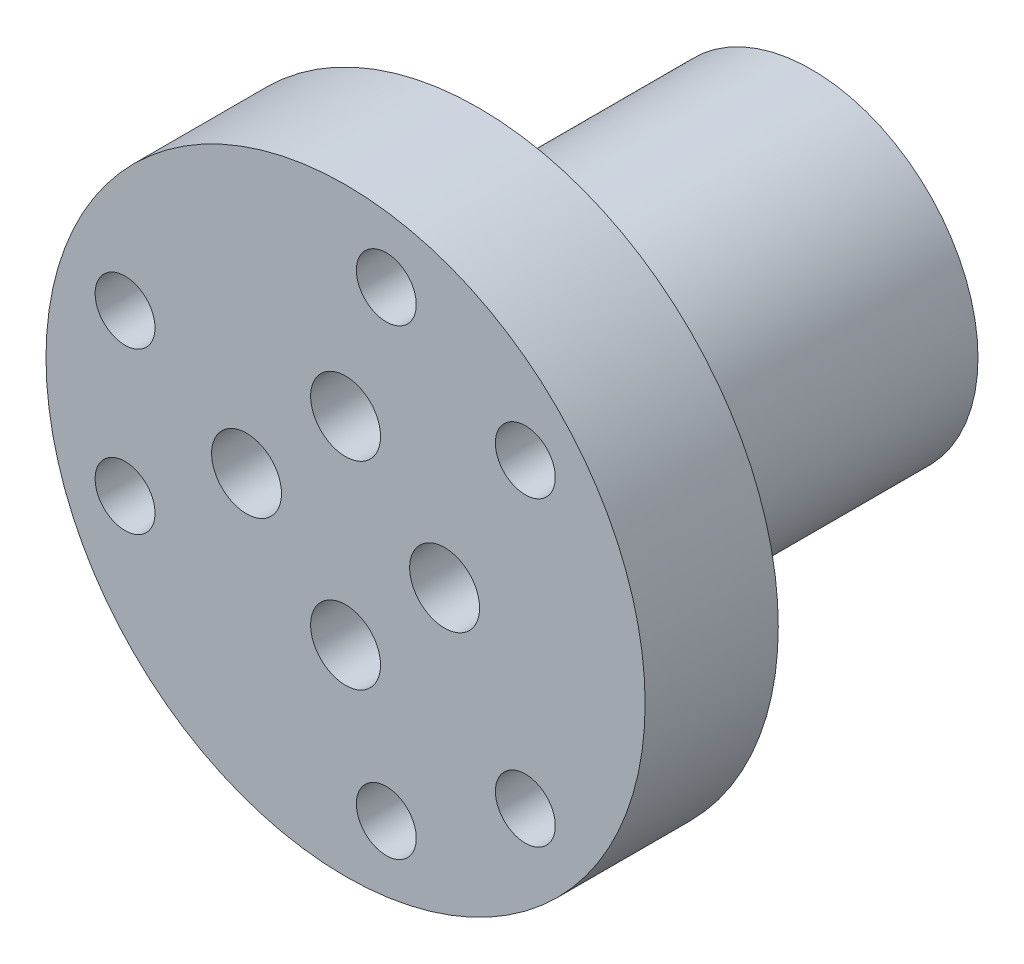
SolidWorks part; units mm, degrees
ref_plane "정면" through (0, 0, 0) normal (0, 0, 1) x (1, 0, 0)
ref_plane "윗면" through (0, 0, 0) normal (0, 1, 0) x (1, 0, 0)
ref_plane "우측면" through (0, 0, 0) normal (1, 0, 0) x (0, 0, -1)
sketch "스케치1" plane through (0, 0, 0) normal (0, 0, 1) x (1, 0, 0)
  line L0 (0, 0) -> (-14.1, 0) construction
  line L1 (0, 0) -> (-13.2497, 4.8225) construction
  circle A0 centre (0, 0) radius 18
  circle A1 centre (0, 5.95) radius 1.3
  circle A2 centre (5.95, 0) radius 1.3
  circle A3 centre (0, -5.95) radius 1.3
  circle A4 centre (-5.95, 0) radius 1.3
  circle A5 centre (0, 0) radius 14.1 construction
  circle A6 centre (-13.2497, 4.8225) radius 1.6
  circle A7 centre (-13.2497, -4.8225) radius 1.6
  circle A8 centre (10.8012, 9.0633) radius 1.6
  circle A9 centre (2.4484, 13.8858) radius 1.6
  circle A10 centre (2.4484, -13.8858) radius 1.6
  circle A11 centre (10.8012, -9.0633) radius 1.6
  point P14 (0, 0)
  point P28 (0, 0)
  dimension "D1" = 36
  dimension "D2" = 2.6
  dimension "D6" = 28.2
  dimension "D7" = 3.2
  dimension "D3" = 5.95
  dimension "D5" = 20
  dimension "D4" = 4
  dimension "D8" = 3
extrude "보스-돌출1" add sketch "스케치1" along normal blind 8
sketch "스케치5" plane through (0, 0, 8) normal (0, 0, 1) x (1, 0, 0)
  circle A0 centre (0, 5.95) radius 2.1
  circle A1 centre (0, -5.95) radius 2.1
  circle A2 centre (5.95, 0) radius 2.1
  circle A3 centre (-5.95, 0) radius 2.1
  dimension "D2" = 4.2
extrude "컷-돌출1" cut sketch "스케치5" against normal blind 6.6
hole_wizard "M3 접시 머리 나사용 카운터싱크2" positions "스케치6" profile "스케치7" countersink size "M3" standard "ISO" end condition through all
sketch "스케치6" plane through (0, 0, 0) normal (0, 0, -1) x (-1, 0, 0)
  point P0 (-2.4484, 13.8858)
  point P3 (13.2497, 4.8225)
  point P6 (13.2497, -4.8225)
  point P9 (-2.4484, -13.8858)
  point P12 (-10.8012, -9.0633)
  point P15 (-10.8012, 9.0633)
sketch "스케치7" plane through (2.4484, 13.8858, 0) normal (1, 0, 0) x (0, 1, 0)
  line L0 (0, 0) -> (0, 8)
  line L1 (0, 8) -> (1.8, 8)
  line L2 (1.8, 8) -> (1.8, 1.35)
  line L3 (1.8, 1.35) -> (3.15, 0)
  line L5 (3.15, 0) -> (0, 0)
  line L6 (-1.8, 1.35) -> (-3.15, 0) construction
  line L11 (0, -6.35) -> (0, 107.95) construction
  dimension "관통 구멍 지름" = 3.6
  dimension "관통 구멍 깊이" = 8
  dimension "표면 카운터싱크 지름" = 6.3
  dimension "표면 카운터싱크 각도" = 90
sketch "스케치8" plane through (0, 0, 0) normal (0, 0, -1) x (-1, 0, 0)
  circle A0 centre (0, 0) radius 10
  circle A1 centre (0, 5.95) radius 1.3
  circle A2 centre (5.95, 0) radius 1.3
  circle A3 centre (0, -5.95) radius 1.3
  circle A4 centre (-5.95, 0) radius 1.3
  dimension "D1" = 20
extrude "보스-돌출2" add sketch "스케치8" along normal blind 2
sketch "스케치9" plane through (0, 0, -2) normal (0, 0, -1) x (-1, 0, 0)
  circle A0 centre (0, 0) radius 10
  circle A1 centre (5.95, 0) radius 2.1
  circle A2 centre (0, 5.95) radius 2.1
  circle A3 centre (-5.95, 0) radius 2.1
  circle A4 centre (0, -5.95) radius 2.1
extrude "보스-돌출3" add sketch "스케치9" along normal blind 18
sketch "스케치10" plane through (0, 0, -20) normal (0, 0, -1) x (-1, 0, 0)
  circle A0 centre (0, -5.95) radius 1.25
  circle A1 centre (-5.95, 0) radius 1.25
  circle A2 centre (0, 5.95) radius 1.25
  circle A3 centre (5.95, 0) radius 1.25
  circle A4 centre (5.95, 0) radius 2.1
  circle A5 centre (0, -5.95) radius 2.1
  circle A6 centre (-5.95, 0) radius 2.1
  circle A7 centre (0, 5.95) radius 2.1
extrude "보스-돌출4" add sketch "스케치10" against normal blind 3.4
sketch "스케치11" plane through (0, 0, 1.4) normal (0, 0, 1) x (1, 0, 0)
  circle A0 centre (5.95, 0) radius 2.1
  circle A1 centre (0, -5.95) radius 2.1
  circle A2 centre (0, 5.95) radius 2.1
  circle A3 centre (-5.95, 0) radius 2.1
extrude "컷-돌출2" cut sketch "스케치11" against normal blind 3.4
